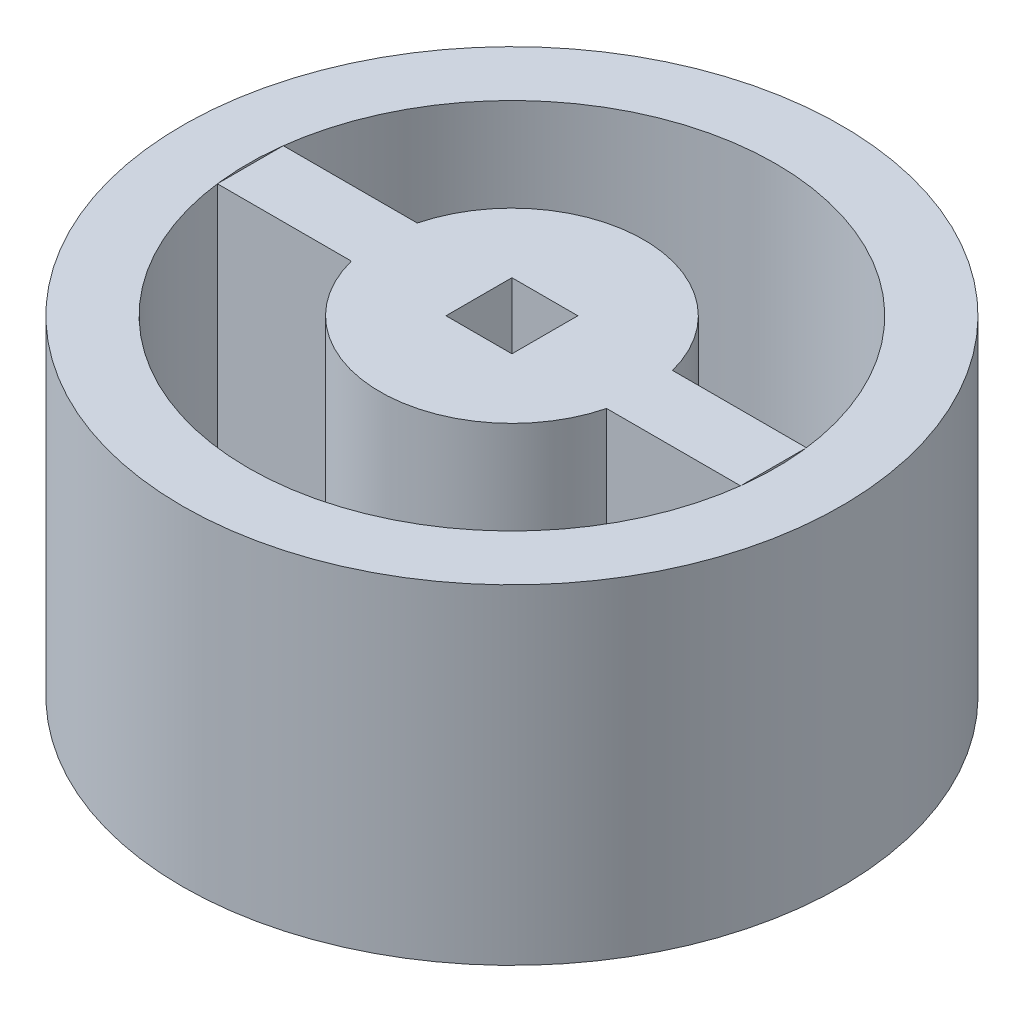
SolidWorks part; units mm, degrees
ref_plane "Front Plane" through (0, 0, 0) normal (0, 0, 1) x (1, 0, 0)
ref_plane "Top Plane" through (0, 0, 0) normal (0, 1, 0) x (1, 0, 0)
ref_plane "Right Plane" through (0, 0, 0) normal (1, 0, 0) x (0, 0, -1)
sketch "Sketch2" plane through (0, 0, 0) normal (0, 1, 0) x (1, 0, 0)
  line L1 (0.5, 0.5) -> (-0.5, 0.5)
  line L2 (0.5, 0.5) -> (0.5, -0.5)
  line L3 (0.5, -0.5) -> (-0.5, -0.5)
  line L4 (-0.5, 0.5) -> (-0.5, -0.5)
  line L5 (0.5, 0.5) -> (-0.5, -0.5) construction
  line L6 (0.5, -0.5) -> (-0.5, 0.5) construction
  circle A0 centre (0, 0) radius 5
  dimension "D1" = 10
  dimension "D2" = 1
extrude "Boss-Extrude1" add sketch "Sketch2" along normal blind 5
sketch "Sketch4" plane through (0, 0, 0) normal (0, -1, 0) x (1, 0, 0)
  circle A0 centre (0, 0) radius 4
  circle A1 centre (0, 0) radius 2
  dimension "D1" = 8
  dimension "D2" = 4
extrude "Cut-Extrude1" cut sketch "Sketch4" against normal through all both and the other way through all
sketch "Sketch6" plane through (0, 5, 0) normal (0, 1, 0) x (1, 0, 0)
  line L1 (-3.9686, -0.5) -> (3.9686, -0.5)
  line L2 (-3.9686, -0.5) -> (-3.9686, 0.5)
  line L3 (-3.9686, 0.5) -> (3.9686, 0.5)
  line L4 (3.9686, -0.5) -> (3.9686, 0.5)
  line L5 (-3.9686, -0.5) -> (3.9686, 0.5) construction
  line L6 (-3.9686, 0.5) -> (3.9686, -0.5) construction
  circle A0 centre (0, 0) radius 4 construction
  point P0 (0, 0)
  dimension "D1" = 1
extrude "Boss-Extrude2" add sketch "Sketch6" against normal blind 5
sketch "Sketch7" plane through (0, 5, 0) normal (0, 1, 0) x (1, 0, 0)
  line L1 (-0.5, -0.5) -> (0.5, -0.5)
  line L2 (-0.5, -0.5) -> (-0.5, 0.5)
  line L3 (-0.5, 0.5) -> (0.5, 0.5)
  line L4 (0.5, -0.5) -> (0.5, 0.5)
  line L5 (-0.5, -0.5) -> (0.5, 0.5) construction
  line L6 (-0.5, 0.5) -> (0.5, -0.5) construction
  point P0 (0, 0)
  dimension "D1" = 1
extrude "Cut-Extrude2" cut sketch "Sketch7" against normal through all both and the other way through all
